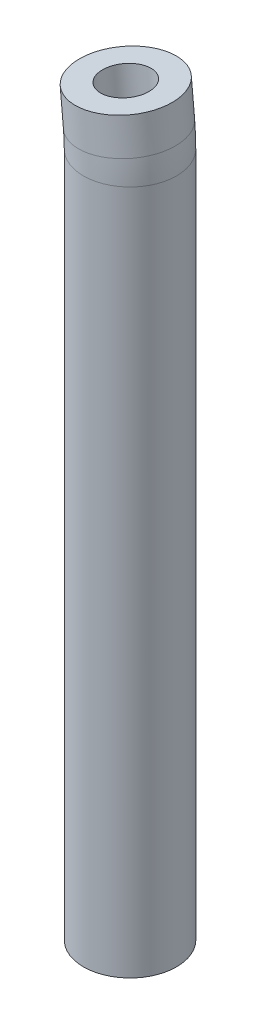
SolidWorks part; units mm, degrees
material "PTFE (general)"
ref_plane "Front Plane" through (0, 0, 0) normal (0, 0, 1) x (1, 0, 0)
ref_plane "Top Plane" through (0, 0, 0) normal (0, 1, 0) x (1, 0, 0)
ref_plane "Right Plane" through (0, 0, 0) normal (1, 0, 0) x (0, 0, -1)
sketch "Sketch1" plane through (0, 0, 0) normal (0, 0, 1) x (1, 0, 0)
  line L0 (0, 0) -> (0, 29.4442)
  line L1 (-0.0415, 30.354) -> (-0.1827, 31.9)
  arc A0 (0, 29.4442) -> (-0.0415, 30.354) centre (-10, 29.4442) ccw
  point P5 (0, 0)
  point P7 (0, 29.9)
  dimension "D4" = 10
  dimension "D1" = 29.9
  dimension "D2" = 2
  dimension "D3" = 5.22
sketch "Sketch2" plane through (0, 0, 0) normal (0, 1, 0) x (1, 0, 0)
  circle A0 centre (0, 0) radius 1
  circle A1 centre (0, 0) radius 2
  dimension "D1" = 4
  dimension "D2" = 2
sweep "Sweep1" add profiles "Sketch2" path "Sketch1"
